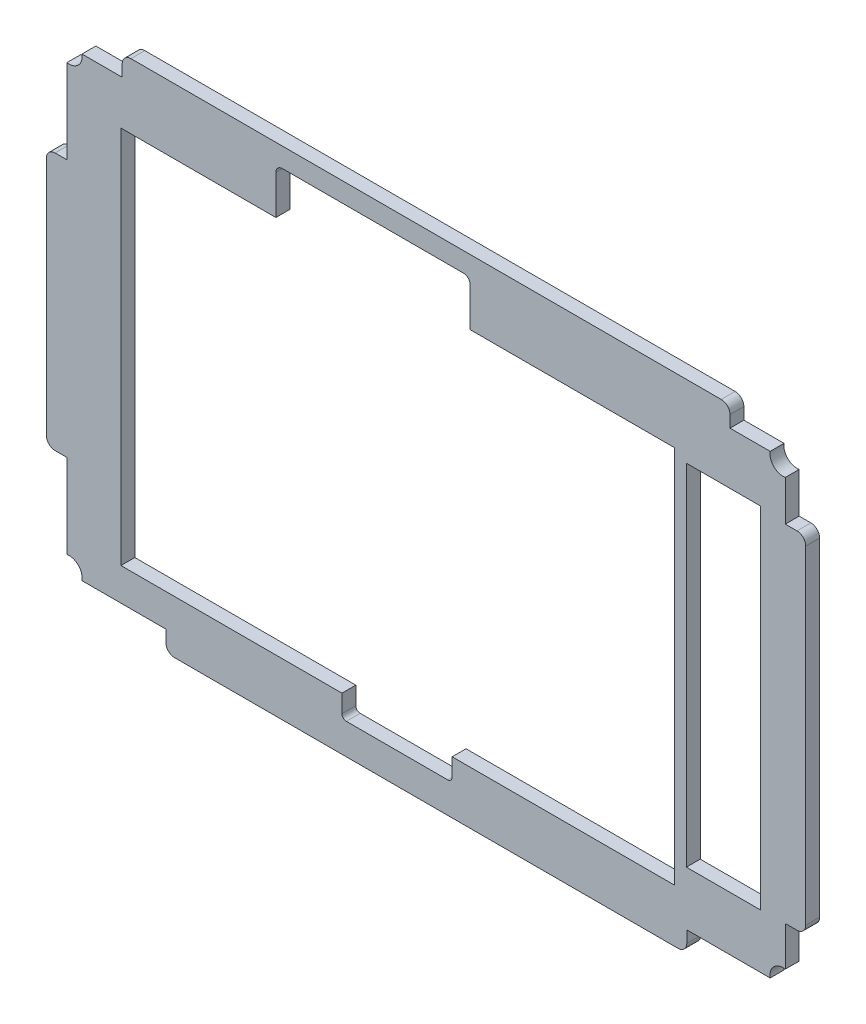
SolidWorks part; units mm, degrees
ref_plane "Front Plane" through (0, 0, 0) normal (0, 0, 1) x (1, 0, 0)
ref_plane "Top Plane" through (0, 0, 0) normal (0, 1, 0) x (1, 0, 0)
ref_plane "Right Plane" through (0, 0, 0) normal (1, 0, 0) x (0, 0, -1)
sketch "Sketch2" plane through (0, 0, 0) normal (0, 0, 1) x (1, 0, 0)
  line L4 (0.0053, 28.4075) -> (0, 0) construction
  line L5 (0, 0) -> (-43.4125, -0.0051) construction
  line L13 (41.075, 26.0649) -> (34.7539, 26.0649)
  line L14 (41.075, 26.0649) -> (41.075, 19.7216)
  line L15 (41.075, -26.0851) -> (29.8135, -26.0851)
  line L16 (-41.075, 26.0649) -> (-41.075, 14.7331)
  line L17 (-40.8256, 30) -> (40.8244, 30.0114) construction
  line L18 (-39.7432, 26.8149) -> (-39.7432, 30.0002) construction
  line L32 (33.7539, 28.4075) -> (-33.7432, 28.4075)
  line L33 (34.7539, 27.4075) -> (34.7539, 26.0649)
  line L34 (-34.7432, 27.4075) -> (-34.7432, 26.0649)
  line L35 (-43.4125, -13.7432) -> (-43.4125, 13.7331)
  line L36 (28.8135, -28.4169) -> (-28.7526, -28.4169)
  line L37 (43.4126, -18.8236) -> (43.4126, 18.7216)
  line L38 (42.4126, 19.7216) -> (41.075, 19.7216)
  line L39 (42.4126, -19.8236) -> (41.075, -19.8236)
  line L40 (29.8135, -27.4169) -> (29.8135, -26.0851)
  line L41 (-29.7526, -27.4169) -> (-29.7526, -26.0851)
  line L42 (-42.4125, -14.7432) -> (-41.075, -14.7432)
  line L43 (-42.4125, 14.7331) -> (-41.075, 14.7331)
  line L44 (-34.7432, 26.0649) -> (-41.075, 26.0649)
  line L45 (41.075, -19.8236) -> (41.075, -26.0851)
  line L46 (-29.7526, -26.0851) -> (-41.075, -26.0851)
  line L47 (-41.075, -14.7432) -> (-41.075, -26.0851)
  arc A0 (42.4126, 19.7216) -> (43.4126, 18.7216) centre (42.4126, 18.7216) cw
  arc A1 (43.4126, -18.8236) -> (42.4126, -19.8236) centre (42.4126, -18.8236) cw
  arc A2 (28.8135, -28.4169) -> (29.8135, -27.4169) centre (28.8135, -27.4169) ccw
  arc A3 (-28.7526, -28.4169) -> (-29.7526, -27.4169) centre (-28.7526, -27.4169) cw
  arc A4 (-42.4125, -14.7432) -> (-43.4125, -13.7432) centre (-42.4125, -13.7432) cw
  arc A5 (-43.4125, 13.7331) -> (-42.4125, 14.7331) centre (-42.4125, 13.7331) cw
  arc A6 (-34.7432, 27.4075) -> (-33.7432, 28.4075) centre (-33.7432, 27.4075) cw
  arc A7 (33.7539, 28.4075) -> (34.7539, 27.4075) centre (33.7539, 27.4075) cw
  point P47 (0.0053, 28.4075)
  point P52 (-43.4125, -0.0051)
  point P55 (0.0304, -28.4169)
  point P58 (43.4126, -0.051)
  point P66 (43.4126, 19.7216)
  point P73 (-29.7526, -28.4169)
  point P78 (-43.4125, 14.7331)
  point P81 (-34.7432, 28.4075)
  dimension "D6" = 1
  dimension "D2" = 1
  dimension "D8" = 1
  dimension "D3" = 1.3426
  dimension "D4" = 6.3211
  dimension "D5" = 6.3432
  dimension "D1" = 67.4971
  dimension "D7" = 1.3376
  dimension "D9" = 37.5452
  dimension "D10" = 1.3376
  dimension "D11" = 6.2615
  dimension "D12" = 11.2615
  dimension "D13" = 57.5661
  dimension "D14" = 11.3224
  dimension "D15" = 11.3419
  dimension "D16" = 27.4763
  dimension "D17" = 1.3375
  dimension "D18" = 11.3318
  dimension "D19" = 6.3318
  dimension "D20" = 28.4075
extrude "Boss-Extrude1" add sketch "Sketch2" along normal blind 1.5875
sketch "Sketch3" plane through (0, 0, 0) normal (0, 0, -1) x (-1, 0, 0)
  line L0 (40.825, 25.825) -> (40.825, -25.825) construction
  line L1 (40.825, -25.825) -> (-40.825, -25.825) construction
  line L2 (-40.825, -25.825) -> (-40.825, 25.825) construction
  line L3 (-40.825, 25.825) -> (40.825, 25.825) construction
  line L4 (0, 0) -> (-40.825, 0) construction
  line L5 (0, 0) -> (0, 25.825) construction
  circle A0 centre (40.825, 25.825) radius 1.5
  circle A1 centre (-40.825, 25.825) radius 1.5
  circle A2 centre (-40.825, -25.825) radius 1.5
  circle A3 centre (40.825, -25.825) radius 1.5
  circle A10 centre (-40.825, 25.825) radius 1.5 construction
  circle A11 centre (-40.825, -25.825) radius 1.5 construction
  circle A12 centre (40.825, -25.825) radius 1.5 construction
  circle A13 centre (40.825, 25.825) radius 1.5 construction
  circle A14 centre (-40.825, 25.825) radius 1.5 construction
  circle A15 centre (-40.825, -25.825) radius 1.5 construction
  circle A16 centre (40.825, -25.825) radius 1.5 construction
  circle A17 centre (40.825, 25.825) radius 1.5 construction
  dimension "D1" = 3
  dimension "D2" = 3
  dimension "D3" = 3
  dimension "D4" = 3
extrude "Cut-Extrude1" cut sketch "Sketch3" against normal blind 1.5875
sketch "Sketch4" plane through (0, 0, 0) normal (0, 0, -1) x (-1, 0, 0)
  line L0 (-28.16, -20.51) -> (-28.16, 20.71) construction
  line L1 (-28.16, 20.71) -> (34.64, 20.71) construction
  line L2 (34.64, -22.11) -> (-28.16, -22.11) construction
  line L3 (-28.16, -22.11) -> (-28.16, -20.51) construction
  line L4 (34.64, -22.11) -> (34.64, -20.51) construction
  line L5 (34.64, 20.71) -> (34.64, -20.51) construction
  line L6 (-28.16, -20.51) -> (-28.16, 20.71) construction
  line L7 (-28.16, 20.71) -> (34.64, 20.71) construction
  line L8 (34.64, -22.11) -> (-28.16, -22.11) construction
  line L9 (-28.16, -22.11) -> (-28.16, -20.51) construction
  line L10 (34.64, -22.11) -> (34.64, -20.51) construction
  line L11 (34.64, 20.71) -> (34.64, -20.51) construction
  line L12 (-28.41, -20.51) -> (-28.41, 20.96)
  line L13 (-28.41, 20.96) -> (34.89, 20.96)
  line L14 (34.89, 20.96) -> (34.89, -20.51)
  line L15 (34.89, -22.36) -> (34.89, -20.51)
  line L16 (34.89, -22.36) -> (-28.41, -22.36)
  line L17 (-28.41, -22.36) -> (-28.41, -20.51)
  line L18 (-28.16, 0.1) -> (-29.7653, 0.1) construction
  line L19 (-38.2653, 20.1) -> (-29.7653, 20.1)
  line L20 (-38.2653, 20.1) -> (-38.2653, -19.9)
  line L21 (-38.2653, -19.9) -> (-29.7653, -19.9)
  line L22 (-29.7653, 20.1) -> (-29.7653, -19.9)
  dimension "D2" = 8.5
  dimension "D3" = 40
  dimension "D1" = 0.25
extrude "Cut-Extrude2" cut sketch "Sketch4" against normal through all
sketch "Sketch6" plane through (0, 0, 0) normal (0, 0, -1) x (-1, 0, 0)
  line L0 (34.89, 20.96) -> (-28.41, 20.96) construction
  line L1 (16.422, 26.18) -> (-4.2808, 26.18)
  line L2 (17.172, 25.43) -> (17.172, 20.96)
  line L3 (17.172, 20.96) -> (-5.0308, 20.96)
  line L4 (-5.0308, 25.43) -> (-5.0308, 20.96)
  line L5 (-28.41, -22.36) -> (34.89, -22.36) construction
  line L6 (-2.9787, -22.36) -> (9.6192, -22.36)
  line L7 (-2.9787, -22.36) -> (-2.9787, -24.4)
  line L8 (-2.4787, -24.9) -> (9.1192, -24.9)
  line L9 (9.6192, -22.36) -> (9.6192, -24.4)
  line L10 (3.3202, -22.36) -> (3.3202, -24.9) construction
  line L11 (-2.9787, -23.38) -> (9.6192, -23.38) construction
  line L12 (6.0706, 26.18) -> (6.0706, 26.0649) construction
  line L13 (-39.3443, 26.0649) -> (-34.7539, 26.0649) construction
  line L14 (41.075, 24.346) -> (41.075, 14.7331) construction
  line L15 (-41.075, 19.7216) -> (-41.075, 24.346) construction
  arc A0 (17.172, 25.43) -> (16.422, 26.18) centre (16.422, 25.43) ccw
  arc A1 (-4.2808, 26.18) -> (-5.0308, 25.43) centre (-4.2808, 25.43) ccw
  arc A2 (-2.4787, -24.9) -> (-2.9787, -24.4) centre (-2.4787, -24.4) cw
  arc A3 (9.1192, -24.9) -> (9.6192, -24.4) centre (9.1192, -24.4) ccw
  dimension "D3" = 0.75
  dimension "D4" = 0.5
  dimension "D1" = 12.5979
  dimension "D2" = 2.54
  dimension "D5" = 22.2028
  dimension "D6" = 5.22
  dimension "D7" = 35.0044
  dimension "D8" = 44.3952
extrude "Cut-Extrude3" cut sketch "Sketch6" against normal through all
